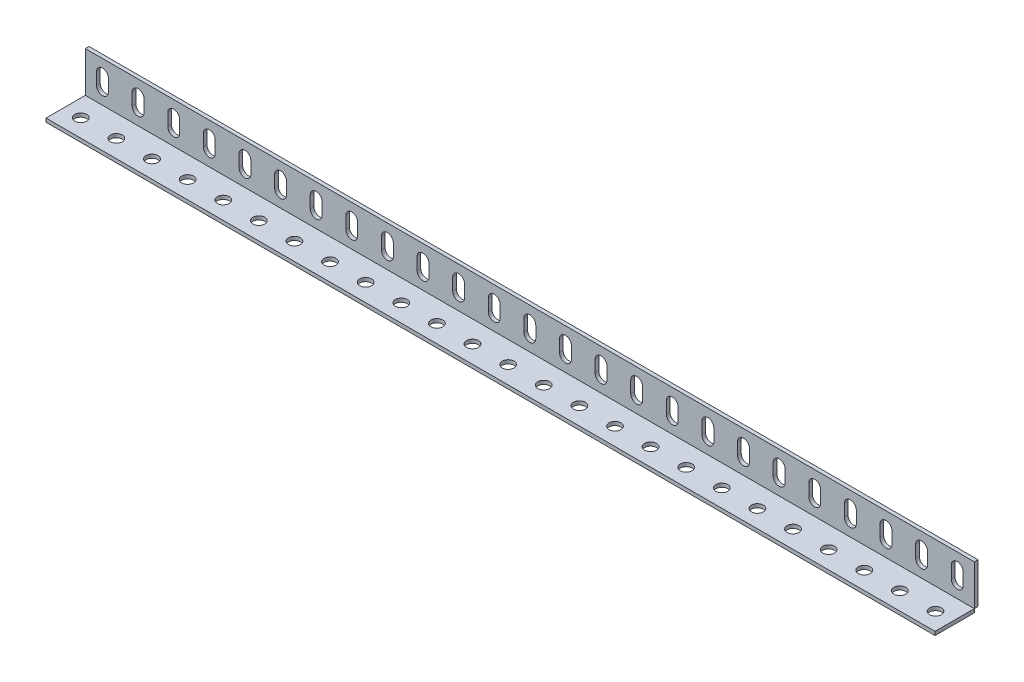
SolidWorks part; units mm, degrees
ref_plane "Front Plane" through (0, 0, 0) normal (0, 0, 1) x (1, 0, 0)
ref_plane "Top Plane" through (0, 0, 0) normal (0, 1, 0) x (1, 0, 0)
ref_plane "Right Plane" through (0, 0, 0) normal (1, 0, 0) x (0, 0, -1)
sketch "Sketch1" plane through (0, 0, 0) normal (0, 0, 1) x (1, 0, 0)
  line L0 (-84.3639, 7.22) -> (-84.3639, -7.22) construction
  line L1 (-78.2539, 2.15) -> (-78.2539, -2.15) construction
  line L2 (-76.1439, 2.15) -> (-76.1439, -2.15)
  line L3 (-80.3639, 2.15) -> (-80.3639, -2.15)
  line L4 (-65.5739, 2.15) -> (-65.5739, -2.15) construction
  line L5 (-63.4639, 2.15) -> (-63.4639, -2.15)
  line L6 (-67.6839, 2.15) -> (-67.6839, -2.15)
  line L7 (-52.8939, 2.15) -> (-52.8939, -2.15) construction
  line L8 (-50.7839, 2.15) -> (-50.7839, -2.15)
  line L9 (-55.0039, 2.15) -> (-55.0039, -2.15)
  line L10 (-40.2139, 2.15) -> (-40.2139, -2.15) construction
  line L11 (-38.1039, 2.15) -> (-38.1039, -2.15)
  line L12 (-42.3239, 2.15) -> (-42.3239, -2.15)
  line L13 (-27.5339, 2.15) -> (-27.5339, -2.15) construction
  line L14 (-25.4239, 2.15) -> (-25.4239, -2.15)
  line L15 (-29.6439, 2.15) -> (-29.6439, -2.15)
  line L16 (-14.8539, 2.15) -> (-14.8539, -2.15) construction
  line L17 (-12.7439, 2.15) -> (-12.7439, -2.15)
  line L18 (-16.9639, 2.15) -> (-16.9639, -2.15)
  line L19 (-2.1739, 2.15) -> (-2.1739, -2.15) construction
  line L20 (-0.0639, 2.15) -> (-0.0639, -2.15)
  line L21 (-4.2839, 2.15) -> (-4.2839, -2.15)
  line L22 (10.5061, 2.15) -> (10.5061, -2.15) construction
  line L23 (12.6161, 2.15) -> (12.6161, -2.15)
  line L24 (8.3961, 2.15) -> (8.3961, -2.15)
  line L25 (23.1861, 2.15) -> (23.1861, -2.15) construction
  line L26 (25.2961, 2.15) -> (25.2961, -2.15)
  line L27 (21.0761, 2.15) -> (21.0761, -2.15)
  line L28 (35.8661, 2.15) -> (35.8661, -2.15) construction
  line L29 (37.9761, 2.15) -> (37.9761, -2.15)
  line L30 (33.7561, 2.15) -> (33.7561, -2.15)
  line L31 (48.5461, 2.15) -> (48.5461, -2.15) construction
  line L32 (50.6561, 2.15) -> (50.6561, -2.15)
  line L33 (46.4361, 2.15) -> (46.4361, -2.15)
  line L34 (61.2261, 2.15) -> (61.2261, -2.15) construction
  line L35 (63.3361, 2.15) -> (63.3361, -2.15)
  line L36 (59.1161, 2.15) -> (59.1161, -2.15)
  line L37 (73.9061, 2.15) -> (73.9061, -2.15) construction
  line L38 (76.0161, 2.15) -> (76.0161, -2.15)
  line L39 (71.7961, 2.15) -> (71.7961, -2.15)
  line L40 (86.5861, 2.15) -> (86.5861, -2.15) construction
  line L41 (88.6961, 2.15) -> (88.6961, -2.15)
  line L42 (84.4761, 2.15) -> (84.4761, -2.15)
  line L43 (99.2661, 2.15) -> (99.2661, -2.15) construction
  line L44 (101.3761, 2.15) -> (101.3761, -2.15)
  line L45 (97.1561, 2.15) -> (97.1561, -2.15)
  line L46 (111.9461, 2.15) -> (111.9461, -2.15) construction
  line L47 (114.0561, 2.15) -> (114.0561, -2.15)
  line L48 (109.8361, 2.15) -> (109.8361, -2.15)
  line L49 (124.6261, 2.15) -> (124.6261, -2.15) construction
  line L50 (126.7361, 2.15) -> (126.7361, -2.15)
  line L51 (122.5161, 2.15) -> (122.5161, -2.15)
  line L52 (137.3061, 2.15) -> (137.3061, -2.15) construction
  line L53 (139.4161, 2.15) -> (139.4161, -2.15)
  line L54 (135.1961, 2.15) -> (135.1961, -2.15)
  line L55 (149.9861, 2.15) -> (149.9861, -2.15) construction
  line L56 (152.0961, 2.15) -> (152.0961, -2.15)
  line L57 (147.8761, 2.15) -> (147.8761, -2.15)
  line L58 (162.6661, 2.15) -> (162.6661, -2.15) construction
  line L59 (164.7761, 2.15) -> (164.7761, -2.15)
  line L60 (160.5561, 2.15) -> (160.5561, -2.15)
  line L61 (175.3461, 2.15) -> (175.3461, -2.15) construction
  line L62 (177.4561, 2.15) -> (177.4561, -2.15)
  line L63 (173.2361, 2.15) -> (173.2361, -2.15)
  line L64 (188.0261, 2.15) -> (188.0261, -2.15) construction
  line L65 (190.1361, 2.15) -> (190.1361, -2.15)
  line L66 (185.9161, 2.15) -> (185.9161, -2.15)
  line L67 (200.7061, 2.15) -> (200.7061, -2.15) construction
  line L68 (202.8161, 2.15) -> (202.8161, -2.15)
  line L69 (198.5961, 2.15) -> (198.5961, -2.15)
  line L70 (213.3861, 2.15) -> (213.3861, -2.15) construction
  line L71 (215.4961, 2.15) -> (215.4961, -2.15)
  line L72 (211.2761, 2.15) -> (211.2761, -2.15)
  line L73 (226.0661, 2.15) -> (226.0661, -2.15) construction
  line L74 (228.1761, 2.15) -> (228.1761, -2.15)
  line L75 (223.9561, 2.15) -> (223.9561, -2.15)
  line L76 (-78.2539, 2.15) -> (-65.5739, 2.15) construction
  line L77 (232.1761, 0) -> (-84.3639, 0) construction
  line L78 (-84.3639, 7.22) -> (232.1761, 7.22) construction
  line L79 (232.1761, 7.22) -> (232.1761, -7.22) construction
  line L80 (232.1761, -7.22) -> (-84.3639, -7.22) construction
  line L82 (-84.3639, 7.22) -> (232.1761, 7.22)
  line L83 (-84.3639, 7.22) -> (-84.3639, -7.22)
  line L84 (-84.3639, -7.22) -> (232.1761, -7.22)
  line L85 (232.1761, 7.22) -> (232.1761, -7.22)
  arc A0 (-76.1439, 2.15) -> (-80.3639, 2.15) centre (-78.2539, 2.15) ccw
  arc A1 (-80.3639, -2.15) -> (-76.1439, -2.15) centre (-78.2539, -2.15) ccw
  arc A2 (-63.4639, 2.15) -> (-67.6839, 2.15) centre (-65.5739, 2.15) ccw
  arc A3 (-67.6839, -2.15) -> (-63.4639, -2.15) centre (-65.5739, -2.15) ccw
  arc A4 (-50.7839, 2.15) -> (-55.0039, 2.15) centre (-52.8939, 2.15) ccw
  arc A5 (-55.0039, -2.15) -> (-50.7839, -2.15) centre (-52.8939, -2.15) ccw
  arc A6 (-38.1039, 2.15) -> (-42.3239, 2.15) centre (-40.2139, 2.15) ccw
  arc A7 (-42.3239, -2.15) -> (-38.1039, -2.15) centre (-40.2139, -2.15) ccw
  arc A8 (-25.4239, 2.15) -> (-29.6439, 2.15) centre (-27.5339, 2.15) ccw
  arc A9 (-29.6439, -2.15) -> (-25.4239, -2.15) centre (-27.5339, -2.15) ccw
  arc A10 (-12.7439, 2.15) -> (-16.9639, 2.15) centre (-14.8539, 2.15) ccw
  arc A11 (-16.9639, -2.15) -> (-12.7439, -2.15) centre (-14.8539, -2.15) ccw
  arc A12 (-0.0639, 2.15) -> (-4.2839, 2.15) centre (-2.1739, 2.15) ccw
  arc A13 (-4.2839, -2.15) -> (-0.0639, -2.15) centre (-2.1739, -2.15) ccw
  arc A14 (12.6161, 2.15) -> (8.3961, 2.15) centre (10.5061, 2.15) ccw
  arc A15 (8.3961, -2.15) -> (12.6161, -2.15) centre (10.5061, -2.15) ccw
  arc A16 (25.2961, 2.15) -> (21.0761, 2.15) centre (23.1861, 2.15) ccw
  arc A17 (21.0761, -2.15) -> (25.2961, -2.15) centre (23.1861, -2.15) ccw
  arc A18 (37.9761, 2.15) -> (33.7561, 2.15) centre (35.8661, 2.15) ccw
  arc A19 (33.7561, -2.15) -> (37.9761, -2.15) centre (35.8661, -2.15) ccw
  arc A20 (50.6561, 2.15) -> (46.4361, 2.15) centre (48.5461, 2.15) ccw
  arc A21 (46.4361, -2.15) -> (50.6561, -2.15) centre (48.5461, -2.15) ccw
  arc A22 (63.3361, 2.15) -> (59.1161, 2.15) centre (61.2261, 2.15) ccw
  arc A23 (59.1161, -2.15) -> (63.3361, -2.15) centre (61.2261, -2.15) ccw
  arc A24 (76.0161, 2.15) -> (71.7961, 2.15) centre (73.9061, 2.15) ccw
  arc A25 (71.7961, -2.15) -> (76.0161, -2.15) centre (73.9061, -2.15) ccw
  arc A26 (88.6961, 2.15) -> (84.4761, 2.15) centre (86.5861, 2.15) ccw
  arc A27 (84.4761, -2.15) -> (88.6961, -2.15) centre (86.5861, -2.15) ccw
  arc A28 (101.3761, 2.15) -> (97.1561, 2.15) centre (99.2661, 2.15) ccw
  arc A29 (97.1561, -2.15) -> (101.3761, -2.15) centre (99.2661, -2.15) ccw
  arc A30 (114.0561, 2.15) -> (109.8361, 2.15) centre (111.9461, 2.15) ccw
  arc A31 (109.8361, -2.15) -> (114.0561, -2.15) centre (111.9461, -2.15) ccw
  arc A32 (126.7361, 2.15) -> (122.5161, 2.15) centre (124.6261, 2.15) ccw
  arc A33 (122.5161, -2.15) -> (126.7361, -2.15) centre (124.6261, -2.15) ccw
  arc A34 (139.4161, 2.15) -> (135.1961, 2.15) centre (137.3061, 2.15) ccw
  arc A35 (135.1961, -2.15) -> (139.4161, -2.15) centre (137.3061, -2.15) ccw
  arc A36 (152.0961, 2.15) -> (147.8761, 2.15) centre (149.9861, 2.15) ccw
  arc A37 (147.8761, -2.15) -> (152.0961, -2.15) centre (149.9861, -2.15) ccw
  arc A38 (164.7761, 2.15) -> (160.5561, 2.15) centre (162.6661, 2.15) ccw
  arc A39 (160.5561, -2.15) -> (164.7761, -2.15) centre (162.6661, -2.15) ccw
  arc A40 (177.4561, 2.15) -> (173.2361, 2.15) centre (175.3461, 2.15) ccw
  arc A41 (173.2361, -2.15) -> (177.4561, -2.15) centre (175.3461, -2.15) ccw
  arc A42 (190.1361, 2.15) -> (185.9161, 2.15) centre (188.0261, 2.15) ccw
  arc A43 (185.9161, -2.15) -> (190.1361, -2.15) centre (188.0261, -2.15) ccw
  arc A44 (202.8161, 2.15) -> (198.5961, 2.15) centre (200.7061, 2.15) ccw
  arc A45 (198.5961, -2.15) -> (202.8161, -2.15) centre (200.7061, -2.15) ccw
  arc A46 (215.4961, 2.15) -> (211.2761, 2.15) centre (213.3861, 2.15) ccw
  arc A47 (211.2761, -2.15) -> (215.4961, -2.15) centre (213.3861, -2.15) ccw
  arc A48 (228.1761, 2.15) -> (223.9561, 2.15) centre (226.0661, 2.15) ccw
  arc A49 (223.9561, -2.15) -> (228.1761, -2.15) centre (226.0661, -2.15) ccw
  point P5 (-78.2539, 0)
  point P14 (-65.5739, 0)
  point P21 (-52.8939, 0)
  point P28 (-40.2139, 0)
  point P35 (-27.5339, 0)
  point P42 (-14.8539, 0)
  point P49 (-2.1739, 0)
  point P56 (10.5061, 0)
  point P63 (23.1861, 0)
  point P70 (35.8661, 0)
  point P77 (48.5461, 0)
  point P84 (61.2261, 0)
  point P91 (73.9061, 0)
  point P98 (86.5861, 0)
  point P105 (99.2661, 0)
  point P112 (111.9461, 0)
  point P119 (124.6261, 0)
  point P126 (137.3061, 0)
  point P133 (149.9861, 0)
  point P140 (162.6661, 0)
  point P147 (175.3461, 0)
  point P154 (188.0261, 0)
  point P161 (200.7061, 0)
  point P168 (213.3861, 0)
  point P175 (226.0661, 0)
  point P182 (-84.3639, 0)
  point P183 (0, 0)
  point P188 (0, 0)
  point P189 (0, 0)
  point P190 (0, 0)
  point P191 (0, 0)
  point P192 (0, 0)
  dimension "D3" = 4.3
  dimension "D8" = 2.15
  dimension "D1" = 14.44
  dimension "D2" = 4.22
  dimension "D5" = 12.68
  dimension "D6" = 4
  dimension "D7" = 4
  dimension "D4" = 25
extrude "Boss-Extrude1" add sketch "Sketch1" along normal blind 1.3
sketch "Sketch3" plane through (0, -7.22, 0) normal (0, -1, 0) x (1, 0, 0)
  line L0 (-84.3639, 1.3) -> (-84.3639, 15.3) construction
  line L1 (-84.3639, 15.3) -> (232.1761, 15.3) construction
  line L2 (232.1761, 15.3) -> (232.1761, 1.3) construction
  line L3 (-84.3639, 15.3) -> (-84.3639, 11.14) construction
  line L4 (-84.3639, 11.14) -> (232.1761, 11.14) construction
  line L5 (-84.3639, 9.03) -> (232.1761, 9.03) construction
  line L6 (-78.2539, 9.03) -> (-65.5739, 9.03) construction
  line L7 (-84.3639, 1.3) -> (232.1761, 1.3) construction
  line L12 (232.1761, 15.3) -> (-84.3639, 15.3)
  line L13 (232.1761, 15.3) -> (232.1761, 1.3)
  line L14 (232.1761, 1.3) -> (-84.3639, 1.3)
  line L15 (-84.3639, 15.3) -> (-84.3639, 1.3)
  circle A0 centre (-78.2539, 9.03) radius 2.11
  circle A1 centre (-65.5739, 9.03) radius 2.11
  circle A2 centre (-52.8939, 9.03) radius 2.11
  circle A3 centre (-40.2139, 9.03) radius 2.11
  circle A4 centre (-27.5339, 9.03) radius 2.11
  circle A5 centre (-14.8539, 9.03) radius 2.11
  circle A6 centre (-2.1739, 9.03) radius 2.11
  circle A7 centre (10.5061, 9.03) radius 2.11
  circle A8 centre (23.1861, 9.03) radius 2.11
  circle A9 centre (35.8661, 9.03) radius 2.11
  circle A10 centre (48.5461, 9.03) radius 2.11
  circle A11 centre (61.2261, 9.03) radius 2.11
  circle A12 centre (73.9061, 9.03) radius 2.11
  circle A13 centre (86.5861, 9.03) radius 2.11
  circle A14 centre (99.2661, 9.03) radius 2.11
  circle A15 centre (111.9461, 9.03) radius 2.11
  circle A16 centre (124.6261, 9.03) radius 2.11
  circle A17 centre (137.3061, 9.03) radius 2.11
  circle A18 centre (149.9861, 9.03) radius 2.11
  circle A19 centre (162.6661, 9.03) radius 2.11
  circle A20 centre (175.3461, 9.03) radius 2.11
  circle A21 centre (188.0261, 9.03) radius 2.11
  circle A22 centre (200.7061, 9.03) radius 2.11
  circle A23 centre (213.3861, 9.03) radius 2.11
  circle A24 centre (226.0661, 9.03) radius 2.11
  point P2 (-84.3639, 9.03)
  point P7 (-76.1439, 9.03)
  point P13 (-80.3639, 9.03)
  point P69 (0, 0)
  point P70 (0, 0)
  point P71 (232.5969, 1.6724)
  point P72 (0, 0)
  point P73 (-84.4549, 1.351)
  point P74 (0, 0)
  point P77 (0, 0)
  point P78 (0, 0)
  dimension "D4" = 4
  dimension "D1" = 14
  dimension "D2" = 4.16
  dimension "D3" = 2.11
  dimension "D6" = 12.68
  dimension "D5" = 25
extrude "Boss-Extrude5" add sketch "Sketch3" along normal blind 1.3 separate body
